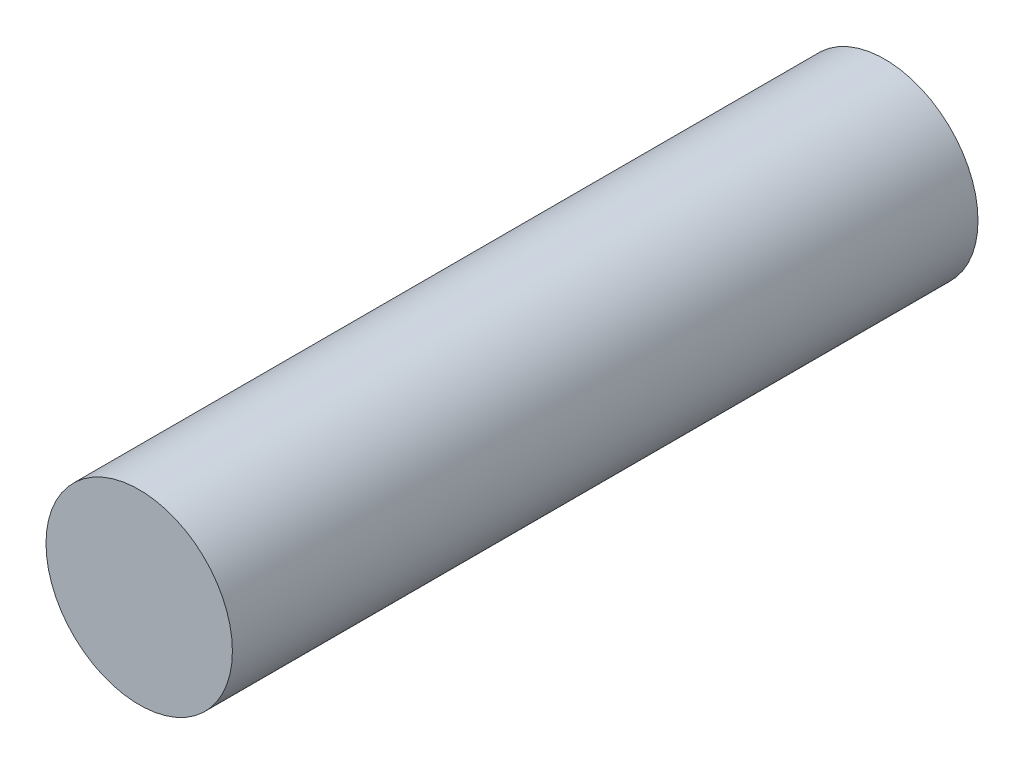
SolidWorks part; units mm, degrees
ref_plane "前视基准面" through (0, 0, 0) normal (0, 0, 1) x (1, 0, 0)
ref_plane "上视基准面" through (0, 0, 0) normal (0, 1, 0) x (1, 0, 0)
ref_plane "右视基准面" through (0, 0, 0) normal (1, 0, 0) x (0, 0, -1)
sketch "草图1" plane through (0, 0, 0) normal (0, 0, 1) x (1, 0, 0)
  circle A0 centre (0, 0) radius 5
  dimension "D1" = 10
extrude "凸台-拉伸1" add sketch "草图1" along normal blind 40
